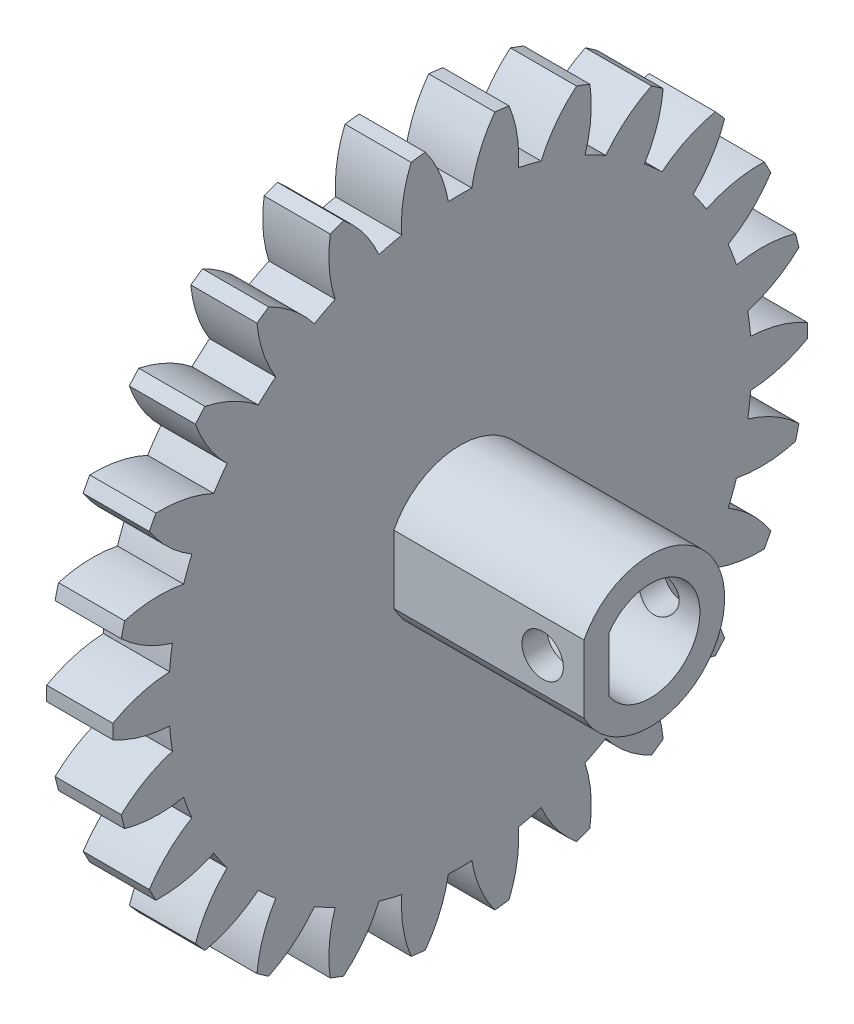
SolidWorks part; units mm, degrees
ref_plane "Plane1" through (0, 0, 0) normal (0, 0, 1) x (1, 0, 0)
ref_plane "Plane2" through (0, 0, 0) normal (0, 1, 0) x (1, 0, 0)
ref_plane "Plane3" through (0, 0, 0) normal (1, 0, 0) x (0, 0, -1)
other "Configuration Table"
sketch "HoldingSke" plane through (0, 0, 0) normal (0, 1, 0) x (1, 0, 0)
  line L0 (0, 0) -> (0.5992, -0.2922)
  line L1 (-15, 0) -> (100, 0) construction
  line L2 (0, 0) -> (-2.1039, 2.3779)
  line L3 (0, 0) -> (-11.863, 4.5341)
  line L4 (0, 0) -> (7.762, 3.7858)
  line L5 (0, 0) -> (-46.8476, -17.4728)
  line L6 (0, 0) -> (-3.3159, -2.2372)
  line L7 (-2.1039, 2.3779) -> (8.6586, 51.2059)
  line L8 (-76.2, 54.61) -> (-75.2, 54.61)
  line L9 (-71.009, 38.7566) -> (-53.1078, 45.2721)
  line L10 (-76.2, 71.12) -> (104.1128, 71.12)
  line L11 (0, 0) -> (-4, 0)
  line L12 (-76.2, 101.6) -> (-76.147, 101.6)
  line L13 (24.9733, 27.94) -> (52.9518, 28.4284)
  line L14 (24.9733, 27.94) -> (24.9743, 27.94)
  line L15 (24.9733, 27.94) -> (100.4006, 29.5858)
  line L16 (-63.627, -1.5) -> (-12.827, -1.5)
  circle A0 centre (0, 0) radius 3
  circle A1 centre (0, 0) radius 17.624
  circle A2 centre (0, 0) radius 37.5
  circle A3 centre (0, 0) radius 3
  dimension "MHD" = 35.248
  dimension "Hub_dia" = 75
  dimension "Bore" = 6
  dimension "MBD" = 6
  dimension "Num_teeth" = 26
  dimension "Pitch" = 0.6667
  dimension "Overall_len" = 50
  dimension "Show_teeth" = 26
  dimension "Thickness" = 4
  dimension "OAL" = 50.0001
  dimension "T_dim" = 1
  dimension "Ap" = 20
  dimension "H" = 19.05
  dimension "Pitch_radius" = 180.3128
  dimension "Width" = 4
  dimension "Backlash" = 0.053
  dimension "Addendum_fac" = 1
  dimension "Dedendum_fac" = 1.25
  dimension "Clearance_fac" = 0.25
  dimension "Dedendum_add" = 0.001
  dimension "Module" = 1.5
sketch "BasProSke" plane through (0, 0, 0) normal (0, 1, 0) x (1, 0, 0)
  line L0 (-10, 0) -> (60, 0) construction
  line L1 (0, 0) -> (0, 21)
  line L2 (0, 0) -> (4, 0)
  line L3 (4, 0) -> (4, 21)
  line L4 (4, 21) -> (0, 21)
  dimension "Thickness" = 4
  dimension "Diameter" = 42
revolve "Base-Revolve" add sketch "BasProSke" angle 360 about L0
sketch "TooCutSke" plane through (0, 0, 0) normal (1, 0, 0) x (0, 0, -1)
  line L1 (0, 0) -> (0, 107) construction
  line L2 (0, 0) -> (-1.2701, 19.4586) construction
  line L3 (0, 0) -> (-4.6937, 38.6557) construction
  line L4 (-1.2701, 19.4586) -> (-2.3468, 19.3279) construction
  arc A0 (0.7092, 17.6097) -> (-0.7092, 17.6097) centre (0, 0) ccw
  arc A1 (2.1199, 20.9183) -> (-2.1199, 20.9183) centre (0, 0) ccw
  circle A2 centre (0, 0) radius 19.5 construction
  circle A3 centre (0, 0) radius 18.324 construction
  arc A4 (-0.7092, 17.6097) -> (-2.1199, 20.9183) centre (-8.3963, 16.2872) ccw
  arc A5 (2.1199, 20.9183) -> (0.7092, 17.6097) centre (8.3963, 16.2872) ccw
  dimension "Root_dia" = 35.248
  dimension "Overcut_dia" = 42.0508
  dimension "Pitch_dia" = 39
  dimension "Base_dia" = 36.648
  dimension "Flank_rad" = 7.8
  dimension "Half_ang" = 6.923
  dimension "Half_CT" = 1.0846
extrude "ToothCut" cut sketch "TooCutSke" along normal through all
fillet "Breaks" [suppressed] radius 0.03
fillet "RootFillets" [suppressed] radius 0.376
pattern_circular "TeethCuts" count 26 every 13.846 about axis through (-10, 0, 0) along (1, 0, 0) of "ToothCut", "RootFillets", "Breaks"
sketch "HubNeaOneSke" plane through (0, 0, 0) normal (-1, 0, 0) x (0, 0, 1)
  circle A0 centre (0, 0) radius 17.624
  dimension "Diameter" = 35.248
extrude "HubNearOne" [suppressed] add sketch "HubNeaOneSke" along normal blind 46.0001
sketch "HubNeaBotSke" plane through (0, 0, 0) normal (-1, 0, 0) x (0, 0, 1)
  circle A0 centre (0, 0) radius 17.624
  dimension "Diameter" = 35.248
extrude "HubNearBoth" [suppressed] add sketch "HubNeaBotSke" along normal blind 23
ref_plane "FarPln" through (4, 0, 0) normal (1, 0, 0) x (0, 0, -1)
sketch "HubFarSke" plane through (4, 0, 0) normal (1, 0, 0) x (0, 0, -1)
  circle A0 centre (0, 0) radius 17.624
  dimension "Diameter" = 35.248
extrude "HubFar" [suppressed] add sketch "HubFarSke" along normal blind 23
sketch "BorSke" plane through (0, 0, 0) normal (1, 0, 0) x (0, 0, -1)
  circle A0 centre (0, 0) radius 3
  dimension "Diameter" = 6
extrude "Bore" cut sketch "BorSke" along normal mid plane 100.0001
sketch "KeySke" plane through (0, 0, 0) normal (1, 0, 0) x (0, 0, -1)
  line L0 (-1, 0) -> (-1, 4)
  line L1 (-1, 4) -> (1, 4)
  line L2 (1, 4) -> (1, 0)
  line L3 (0, 0) -> (0, 34) construction
  line L4 (-1, 0) -> (1, 0)
  dimension "Offset" = 4
  dimension "Width" = 2
extrude "Keyway" [suppressed] cut sketch "KeySke" along normal mid plane 100.0001
pattern_circular "Keyway2" [suppressed] count 2 every 90 about axis through (-10, 0, 0) along (1, 0, 0)
sketch "草图1" plane through (4, 0, 0) normal (1, 0, 0) x (0, 0, -1)
  line L0 (-2.5055, 1.65) -> (-2.5055, -1.65)
  line L1 (-4.0055, 2.0509) -> (-4.0055, -2.0509)
  arc A2 (-2.5055, 1.65) -> (-2.5055, -1.65) centre (0, 0) cw
  arc A3 (-4.0055, 2.0509) -> (-4.0055, -2.0509) centre (0, 0) cw
  point P7 (-3.7225, -2.5383)
  point P8 (0, 0)
  point P9 (-3.739, -2.504)
  dimension "D1" = 3
  dimension "D2" = 4.5
  dimension "D3" = 3.3
  dimension "D4" = 1.5
extrude "凸台-拉伸1" add sketch "草图1" along normal blind 11.5
sketch "草图2" plane through (0, 0, 4.0055) normal (0, 0, 1) x (1, 0, 0)
  line L0 (15.5, 0) -> (13, 0) construction
  line L1 (15.5, 2.0509) -> (15.5, -2.0509) construction
  circle A0 centre (13, 0) radius 1.25
  dimension "D2" = 2.5
  dimension "D1" = 2.5
extrude "切除-拉伸1" cut sketch "草图2" against normal through all
equation "' \"Module@HoldingSke\" = 6.35"
equation "' \"Num_teeth@HoldingSke\" = 12"
equation "' \"Ap@HoldingSke\" =  20"
equation "' \"Ap@HoldingSke\" = 20"
equation "' \"Width@HoldingSke\" = 0.5 * 25.4"
equation "' \"Hub_dia@HoldingSke\"= 1 * 25.4"
equation "' \"Hub_dia@HoldingSke\" = 1 * 25.4"
equation "' \"Overall_len@HoldingSke\" = 1.0 * 25.4"
equation "' \"Bore@HoldingSke\" = 0.75 * 25.4"
equation "' \"T_dim@HoldingSke\" = 0.1 * 25.4"
equation "' \"Width@KeySke\" = 0.25 * 25.4"
equation "' \"Show_teeth@HoldingSke\" = 13"
equation "' \"Backlash@HoldingSke\" = 0.009 * 25.4"
equation "' \"Addendum_fac@HoldingSke\" = 1.0"
equation "' \"Dedendum_fac@HoldingSke\" = 1.25"
equation "' \"Dedendum_add@HoldingSke\" = 0.00005 * 25.4"
equation "' \"Clearance_fac@HoldingSke\" = 0.25"
equation "\"Pitch@HoldingSke\" = 1 / \"Module@HoldingSke\""
equation "\"Overcut_dia@TooCutSke\" = (\"Num_teeth@HoldingSke\" + 2 * \"Addendum_fac@HoldingSke\") / \"Pitch@HoldingSke\" + 0.002 * 25.4"
equation "\"Pitch_dia@TooCutSke\" = \"Num_teeth@HoldingSke\" / \"Pitch@HoldingSke\""
equation "\"Base_dia@TooCutSke\" = \"Num_teeth@HoldingSke\" / \"Pitch@HoldingSke\" * cos((\"Ap@HoldingSke\"  * 3.14159265 / 180))"
equation "\"Root_dia@TooCutSke\" = (\"Num_teeth@HoldingSke\" + 2) / \"Pitch@HoldingSke\" - 2 * (\"Addendum_fac@HoldingSke\" + \"Dedendum_fac@HoldingSke\") / \"Pitch@HoldingSke\" - \"Dedendum_add@HoldingSke\" * 2"
equation "\"Half_ang@TooCutSke\" = 180 / \"Num_teeth@HoldingSke\""
equation "\"Half_CT@TooCutSke\" = \"Num_teeth@HoldingSke\" / \"Pitch@HoldingSke\" * sin((3.14159265 / 2 / \"Num_teeth@HoldingSke\")) / 2 - 7 * \"Backlash@HoldingSke\" / 4"
equation "\"Flank_rad@TooCutSke\" = \"Num_teeth@HoldingSke\" / \"Pitch@HoldingSke\" / 5"
equation "\"Radius@RootFillets\" = \"Clearance_fac@HoldingSke\" / \"Pitch@HoldingSke\" + \"Dedendum_add@HoldingSke\""
equation "\"Break_rad@Breaks\" = 0.02 / \"Pitch@HoldingSke\""
equation "\"Thickness@HoldingSke\" = \"Width@HoldingSke\""
equation "\"OAL@HoldingSke\" = \"Thickness@HoldingSke\""
equation "\"MHD@HoldingSke\" = (\"Num_teeth@HoldingSke\" + 2) / \"Pitch@HoldingSke\" - 2 * (\"Addendum_fac@HoldingSke\" + \"Dedendum_fac@HoldingSke\")  / \"Pitch@HoldingSke\" - \"Dedendum_add@HoldingSke\" * 2"
equation "\"MBD@HoldingSke\" = (\"Num_teeth@HoldingSke\" + 2) / \"Pitch@HoldingSke\" - 2 * (\"Addendum_fac@HoldingSke\" + \"Dedendum_fac@HoldingSke\")  / \"Pitch@HoldingSke\" - \"Dedendum_add@HoldingSke\" * 2 - 0.002 * 25.4"
equation "\"MHD@HoldingSke\" = ((sgn( \"MHD@HoldingSke\" - \"Hub_dia@HoldingSke\" )-1)*( \"MHD@HoldingSke\" - \"Hub_dia@HoldingSke\" ))/-2+ \"Hub_dia@HoldingSke\""
equation "\"MBD@HoldingSke\" = ((sgn( \"MBD@HoldingSke\" - \"Bore@HoldingSke\" )-1)*( \"MBD@HoldingSke\" - \"Bore@HoldingSke\" ))/-2+ \"Bore@HoldingSke\""
equation "\"OAL@HoldingSke\" = ((sgn( \"OAL@HoldingSke\" - \"Overall_len@HoldingSke\" )+1)*( \"OAL@HoldingSke\" - \"Overall_len@HoldingSke\" ))/2 + \"Overall_len@HoldingSke\" + 0.000002 * 25.4"
equation "\"Num_teeth@TeethCuts\" = int( \"Show_teeth@HoldingSke\" ) + 1"
equation "\"Num_teeth@TeethCuts\" = ((sgn( \"Num_teeth@TeethCuts\" - \"Num_teeth@HoldingSke\" )-1)*( \"Num_teeth@TeethCuts\" - \"Num_teeth@HoldingSke\" ))/-2+ \"Num_teeth@HoldingSke\""
equation "\"Num_teeth@TeethCuts\" = ((sgn( \"Num_teeth@TeethCuts\" - 2.0)+1)*( \"Num_teeth@TeethCuts\" - 2.0))/2 +2.0"
equation "\"Angle@TeethCuts\" = 360.0 / \"Num_teeth@HoldingSke\""
equation "\"Diameter@BasProSke\" = (\"Num_teeth@HoldingSke\" + 2 * \"Addendum_fac@HoldingSke\") / \"Pitch@HoldingSke\""
equation "\"Thickness@BasProSke\"  = \"Thickness@HoldingSke\""
equation "' \"Fillet_rad@BasProSke\" =  \"Thickness@HoldingSke\" * 0.05"
equation "' \"Fillet_rad@BasProSke\" = \"Thickness@HoldingSke\" * 0.05"
equation "\"MHD@HoldingSke\" = ((sgn( \"MHD@HoldingSke\" - \"Root_dia@TooCutSke\" )-1)*( \"MHD@HoldingSke\" - \"Root_dia@TooCutSke\" ))/-2+ \"Root_dia@TooCutSke\""
equation "\"Diameter@HubNeaOneSke\" = \"MHD@HoldingSke\""
equation "\"Length@HubNearOne\" = \"OAL@HoldingSke\" - \"Thickness@BasProSke\""
equation "\"Diameter@HubNeaBotSke\" = \"MHD@HoldingSke\""
equation "\"Length@HubNearBoth\" = ( \"OAL@HoldingSke\" - \"Thickness@BasProSke\" ) / 2.0"
equation "\"Thickness@FarPln\" = \"Thickness@BasProSke\""
equation "\"Diameter@HubFarSke\" = \"MHD@HoldingSke\""
equation "\"Length@HubFar\" = ( \"OAL@HoldingSke\" - \"Thickness@BasProSke\" ) / 2.0"
equation "\"Diameter@BorSke\" = \"MBD@HoldingSke\""
equation "\"D1@Bore\" = \"OAL@HoldingSke\" * 2.0"
equation "\"D1@Keyway\" = \"OAL@HoldingSke\" * 2.0"
equation "\"Offset@KeySke\" = \"T_dim@HoldingSke\" + \"MBD@HoldingSke\" / 2.0"
